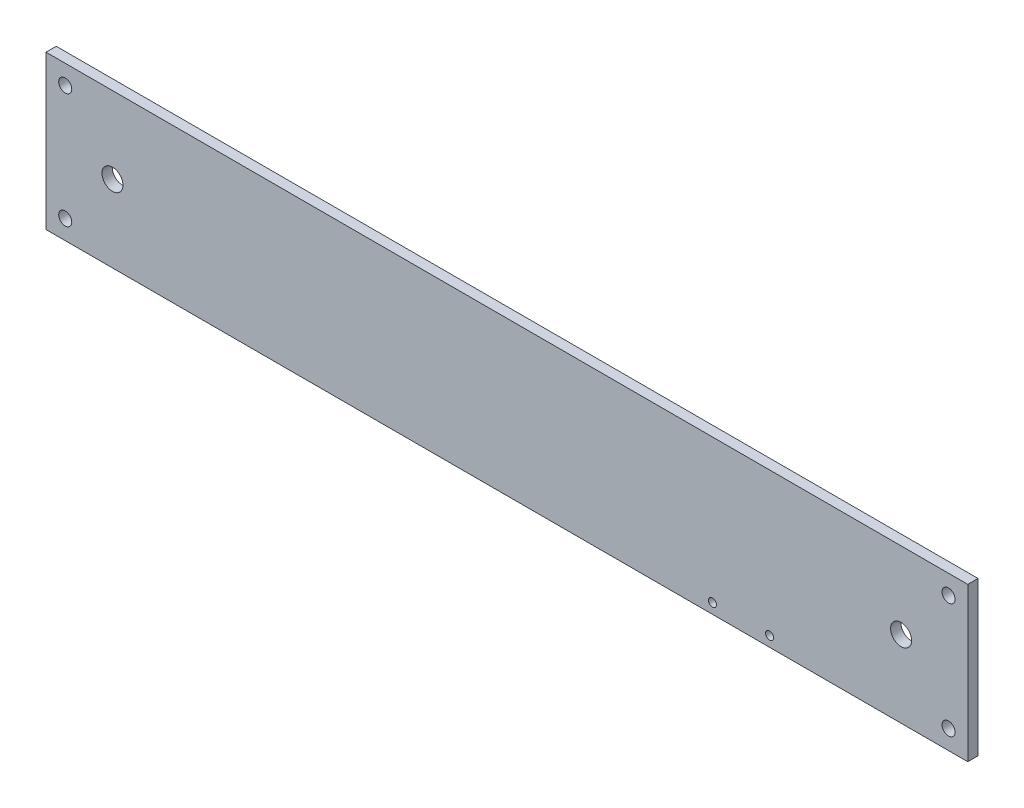
SolidWorks part; units mm, degrees
ref_plane "Front Plane" through (0, 0, 0) normal (0, 0, 1) x (1, 0, 0)
ref_plane "Top Plane" through (0, 0, 0) normal (0, 1, 0) x (1, 0, 0)
ref_plane "Right Plane" through (0, 0, 0) normal (1, 0, 0) x (0, 0, -1)
sketch "Sketch1" plane through (0, 0, 0) normal (0, 0, 1) x (1, 0, 0)
  line L4 (334.0413, -30) -> (334.0413, 30)
  line L5 (-25.9587, -30) -> (334.0413, -30)
  line L6 (-25.9587, 30) -> (-25.9587, -30)
  line L7 (334.0413, 30) -> (-25.9587, 30)
  line L8 (334.0413, -30) -> (334.0413, 30)
  line L9 (-25.9587, -30) -> (334.0413, -30)
  line L10 (-25.9587, 30) -> (-25.9587, -30)
  line L11 (334.0413, 30) -> (-25.9587, 30)
  circle A0 centre (0, 0) radius 4.1
  circle A1 centre (308, 0) radius 4.1
  circle A2 centre (-18.4514, 22.4927) radius 2.55 construction
  circle A3 centre (-18.4514, -22.4927) radius 2.55 construction
  circle A4 centre (326.5339, 22.4927) radius 2.55 construction
  circle A5 centre (326.5339, -22.4927) radius 2.55 construction
  circle A6 centre (-18.4514, 22.4927) radius 2.55
  circle A7 centre (-18.4514, -22.4927) radius 2.55
  circle A8 centre (326.5339, 22.4927) radius 2.55
  circle A9 centre (326.5339, -22.4927) radius 2.55
  dimension "D2" = 8.2
  dimension "D3" = 8.2
  dimension "D1" = 0
extrude "Boss-Extrude1" add sketch "Sketch1" along normal blind 4
sketch "Sketch3" plane through (0, 0, 4) normal (0, 0, 1) x (1, 0, 0)
  circle A6 centre (256.65, -26) radius 1.55
  circle A7 centre (234.35, -26) radius 1.55
  circle A8 centre (234.35, -26) radius 1.55 construction
  circle A9 centre (256.65, -26) radius 1.55 construction
  dimension "D1" = 3.1
  dimension "D2" = 3.1
extrude "Cut-Extrude2" cut sketch "Sketch3" against normal blind 4
